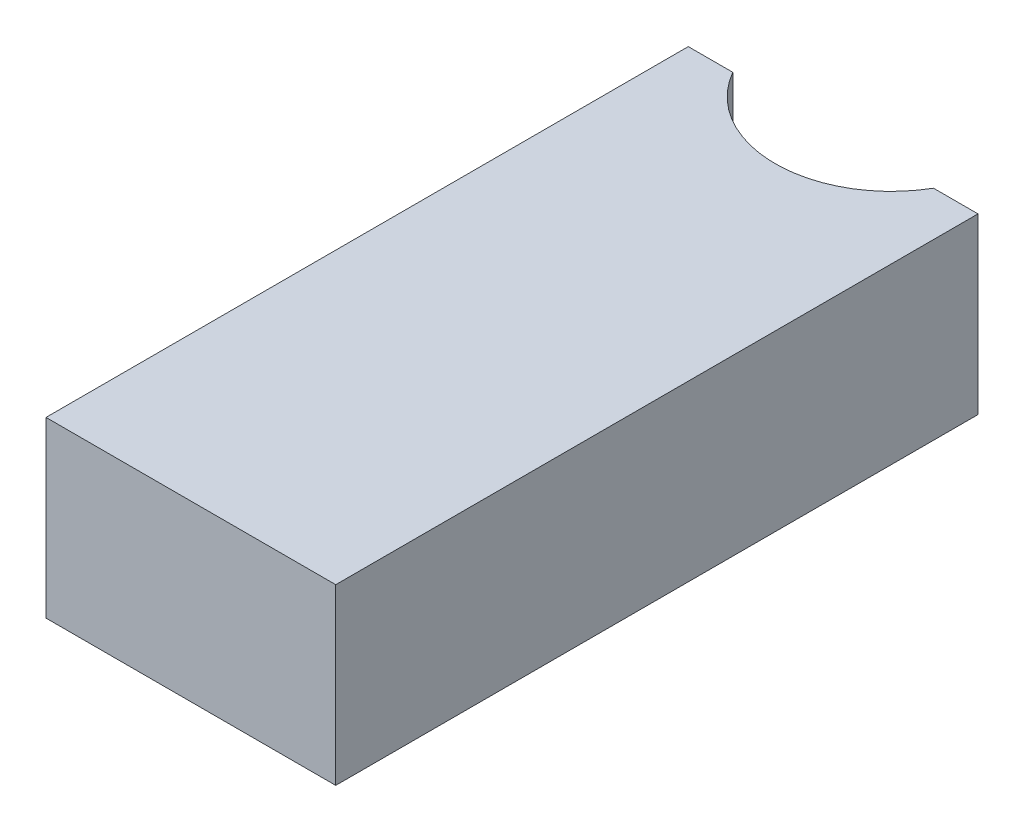
SolidWorks part; units mm, degrees
material "Custom Plastic"
ref_plane "X-Y Datum" through (0, 0, 0) normal (0, 0, 1) x (1, 0, 0)
ref_plane "X-Z Datum" through (0, 0, 0) normal (0, 1, 0) x (1, 0, 0)
ref_plane "Y-Z Datum" through (0, 0, 0) normal (1, 0, 0) x (0, 0, -1)
sketch "Sketch1" plane through (0, 0, 0) normal (0, 0, 1) x (1, 0, 0)
  line L1 (-15.875, 9.525) -> (15.875, 9.525)
  line L2 (-15.875, 9.525) -> (-15.875, -9.525)
  line L3 (-15.875, -9.525) -> (15.875, -9.525)
  line L4 (15.875, 9.525) -> (15.875, -9.525)
  line L5 (-15.875, 9.525) -> (15.875, -9.525) construction
  line L6 (-15.875, -9.525) -> (15.875, 9.525) construction
  point P0 (0, 0)
  dimension "D1" = 31.75
  dimension "D2" = 19.05
extrude "Boss-Extrude1" add sketch "Sketch1" along normal blind 70.3834
sketch "Sketch2" plane through (0, 9.525, 0) normal (0, 1, 0) x (1, 0, 0)
  circle A0 centre (0, 6.35) radius 12.7
  point P2 (0, -6.35)
  dimension "D1" = 25.4
  dimension "D2" = 6.35
extrude "Cut-Extrude1" cut sketch "Sketch2" against normal through all
